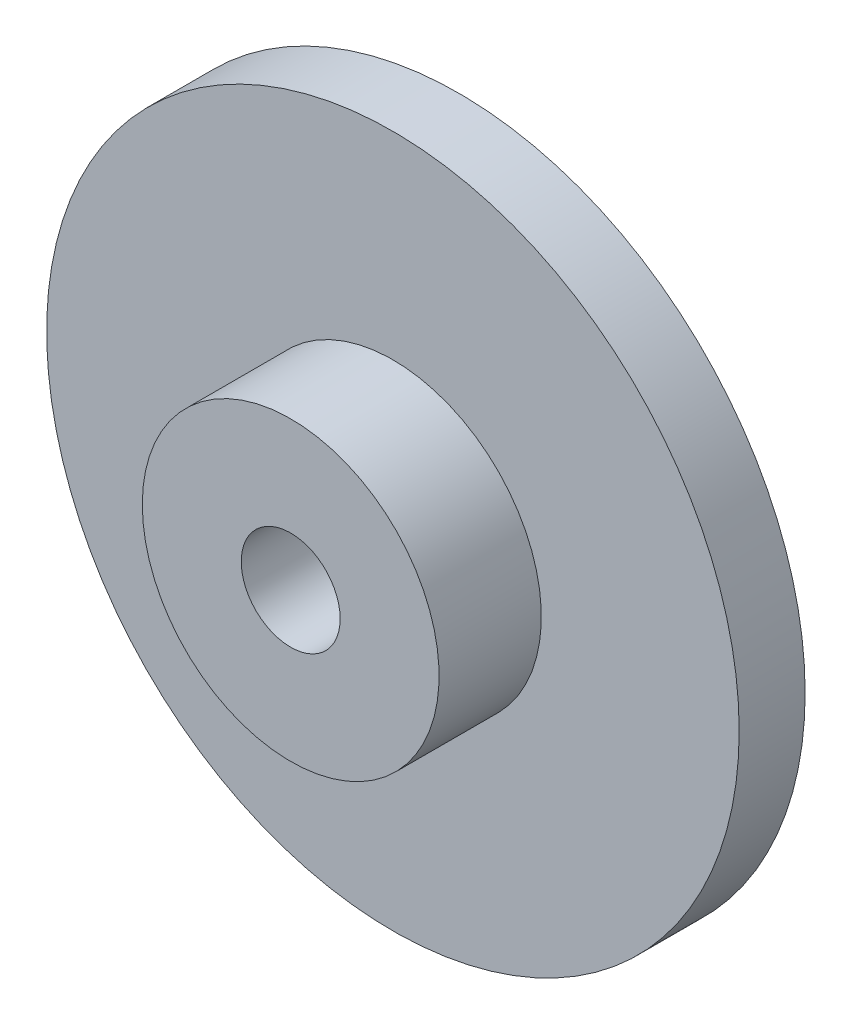
SolidWorks part; units mm, degrees
ref_plane "Alzado" through (0, 0, 0) normal (0, 0, 1) x (1, 0, 0)
ref_plane "Planta" through (0, 0, 0) normal (0, 1, 0) x (1, 0, 0)
ref_plane "Vista lateral" through (0, 0, 0) normal (1, 0, 0) x (0, 0, -1)
sketch "Croquis1" plane through (0, 0, 0) normal (0, 0, 1) x (1, 0, 0)
  circle A0 centre (0, 0) radius 10.5
extrude "Saliente-Extruir1" add sketch "Croquis1" along normal blind 2
sketch "Croquis2" plane through (0, 0, 2) normal (0, 0, 1) x (1, 0, 0)
  circle A0 centre (0, 0) radius 4.5
extrude "Saliente-Extruir2" add sketch "Croquis2" along normal blind 3.1
sketch "Croquis3" plane through (0, 0, 5.1) normal (0, 0, 1) x (1, 0, 0)
  circle A0 centre (0, 0) radius 1.5
extrude "Cortar-Extruir1" cut sketch "Croquis3" against normal up to next
